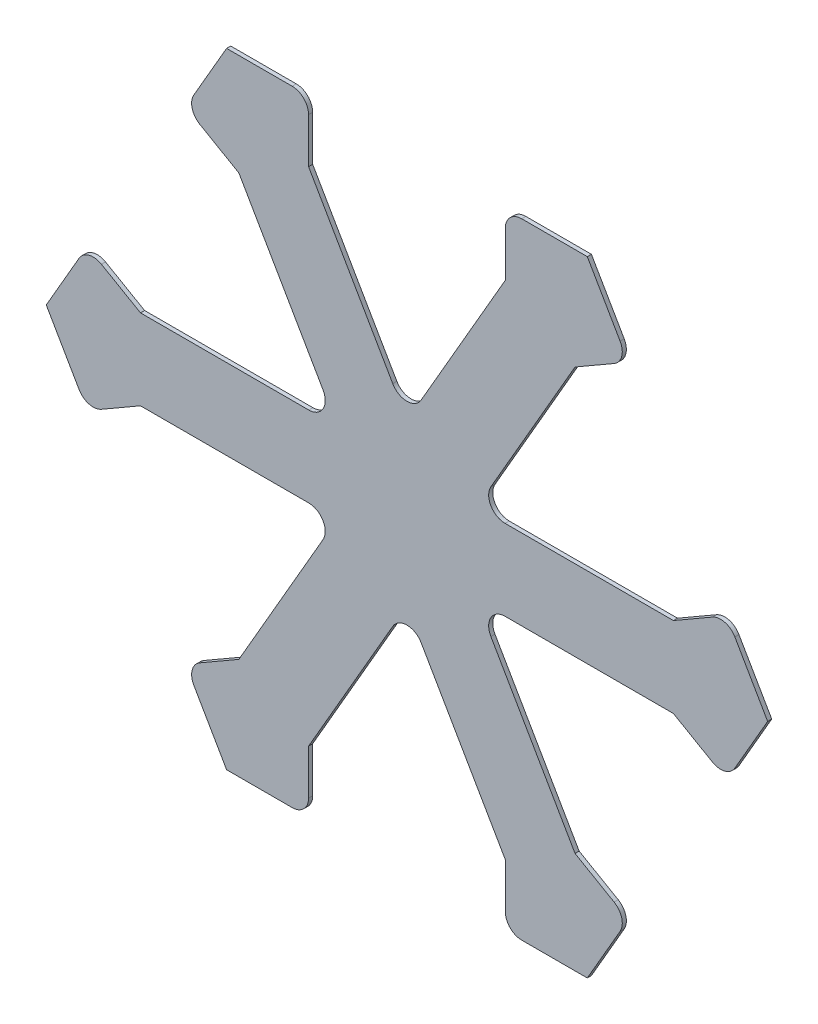
SolidWorks part; units mm, degrees
material "1.0037 (S235JR)"
ref_plane "Plan de face" through (0, 0, 0) normal (0, 0, 1) x (1, 0, 0)
ref_plane "Plan de dessus" through (0, 0, 0) normal (0, 1, 0) x (1, 0, 0)
ref_plane "Plan de droite" through (0, 0, 0) normal (1, 0, 0) x (0, 0, -1)
sketch "Esquisse2" plane through (0, 0, 0) normal (0, 0, 1) x (1, 0, 0)
  line L0 (-440, 0) -> (-400, -69.282)
  line L1 (-372.6795, -76.6025) -> (-325.0481, -49.1025)
  line L3 (-400, 69.282) -> (-440, 0)
  line L4 (-372.6795, 76.6025) -> (-325.0481, 49.1025)
  line L25 (-325.0481, 49.1025) -> (-119.6891, 49.1025)
  line L36 (-119.6891, -49.1025) -> (-325.0481, -49.1025)
  line L37 (-85.0481, 49.1025) -> (-85.0481, -49.1025) construction
  line L38 (-220, 381.0512) -> (-260, 311.7691)
  line L39 (-252.6795, 284.4486) -> (-205.0481, 256.9486)
  line L40 (-140, 381.0512) -> (-220, 381.0512)
  line L41 (-120, 361.0512) -> (-120, 306.0512)
  line L42 (-120, 306.0512) -> (-17.3205, 128.2051)
  line L43 (-102.3686, 79.1025) -> (-205.0481, 256.9486)
  line L44 (0, 98.2051) -> (-85.0481, 49.1025) construction
  line L45 (220, 381.0512) -> (140, 381.0512)
  line L46 (120, 361.0512) -> (120, 306.0512)
  line L47 (260, 311.7691) -> (220, 381.0512)
  line L48 (252.6795, 284.4486) -> (205.0481, 256.9486)
  line L49 (205.0481, 256.9486) -> (102.3686, 79.1025)
  line L50 (17.3205, 128.2051) -> (120, 306.0512)
  line L51 (85.0481, 49.1025) -> (0, 98.2051) construction
  line L52 (440, 0) -> (400, 69.282)
  line L53 (372.6795, 76.6025) -> (325.0481, 49.1025)
  line L54 (400, -69.282) -> (440, 0)
  line L55 (372.6795, -76.6025) -> (325.0481, -49.1025)
  line L56 (325.0481, -49.1025) -> (119.6891, -49.1025)
  line L57 (119.6891, 49.1025) -> (325.0481, 49.1025)
  line L58 (85.0481, -49.1025) -> (85.0481, 49.1025) construction
  line L59 (220, -381.0512) -> (260, -311.7691)
  line L60 (252.6795, -284.4486) -> (205.0481, -256.9486)
  line L61 (140, -381.0512) -> (220, -381.0512)
  line L62 (120, -361.0512) -> (120, -306.0512)
  line L63 (120, -306.0512) -> (17.3205, -128.2051)
  line L64 (102.3686, -79.1025) -> (205.0481, -256.9486)
  line L65 (0, -98.2051) -> (85.0481, -49.1025) construction
  line L66 (-220, -381.0512) -> (-140, -381.0512)
  line L67 (-120, -361.0512) -> (-120, -306.0512)
  line L68 (-260, -311.7691) -> (-220, -381.0512)
  line L69 (-252.6795, -284.4486) -> (-205.0481, -256.9486)
  line L70 (-205.0481, -256.9486) -> (-102.3686, -79.1025)
  line L71 (-17.3205, -128.2051) -> (-120, -306.0512)
  line L72 (-85.0481, -49.1025) -> (0, -98.2051) construction
  line L73 (-223.2362, 330.4459) -> (-397.7927, 28.1052) construction
  arc A0 (102.3686, 79.1025) -> (119.6891, 49.1025) centre (119.6891, 69.1025) ccw
  arc A1 (119.6891, -49.1025) -> (102.3686, -79.1025) centre (119.6891, -69.1025) ccw
  arc A2 (17.3205, -128.2051) -> (-17.3205, -128.2051) centre (0, -138.2051) ccw
  arc A3 (-102.3686, -79.1025) -> (-119.6891, -49.1025) centre (-119.6891, -69.1025) ccw
  arc A4 (-17.3205, 128.2051) -> (17.3205, 128.2051) centre (0, 138.2051) ccw
  arc A5 (-102.3686, 79.1025) -> (-119.6891, 49.1025) centre (-119.6891, 69.1025) cw
  arc A6 (-260, -311.7691) -> (-252.6795, -284.4486) centre (-242.6795, -301.7691) cw
  arc A7 (-140, -381.0512) -> (-120, -361.0512) centre (-140, -361.0512) ccw
  arc A8 (140, -381.0512) -> (120, -361.0512) centre (140, -361.0512) cw
  arc A9 (260, -311.7691) -> (252.6795, -284.4486) centre (242.6795, -301.7691) ccw
  arc A10 (400, -69.282) -> (372.6795, -76.6025) centre (382.6795, -59.282) cw
  arc A11 (400, 69.282) -> (372.6795, 76.6025) centre (382.6795, 59.282) ccw
  arc A12 (260, 311.7691) -> (252.6795, 284.4486) centre (242.6795, 301.7691) cw
  arc A13 (140, 381.0512) -> (120, 361.0512) centre (140, 361.0512) ccw
  arc A14 (-140, 381.0512) -> (-120, 361.0512) centre (-140, 361.0512) cw
  arc A15 (-260, 311.7691) -> (-252.6795, 284.4486) centre (-242.6795, 301.7691) ccw
  arc A16 (-400, -69.282) -> (-372.6795, -76.6025) centre (-382.6795, -59.282) ccw
  arc A17 (-372.6795, 76.6025) -> (-400, 69.282) centre (-382.6795, 59.282) ccw
  point P2 (-85.0481, 0)
  point P6 (0, 0)
  point P12 (-42.524, 73.6538)
  point P21 (42.524, 73.6538)
  point P29 (85.0481, 0)
  point P37 (0.1928, -8.2278)
  point P38 (42.524, -73.6538)
  point P47 (-42.524, -73.6538)
  point P53 (0, 0)
  point P88 (-390, -86.6025)
  point P91 (-390, 86.6025)
  dimension "D8" = 6
  dimension "D9" = 20
  dimension "D10" = 20
  dimension "D1" = 120
  dimension "D2" = 100
  dimension "D3" = 100
  dimension "D4" = 75
  dimension "D5" = 75
  dimension "D6" = 90
  dimension "D7" = 440
extrude "Boss.-Extru.2" add sketch "Esquisse2" along normal blind 5 contours L71 L63 L62 L61 L59 L60 L64 L56 L55 L54 L52 L53 L57 L49 L48 L47 L45 L46 L50 L42 L41 L40 L38 L39 L43 L25 L4 L3 L0 L1 L36 L70 L69 L68 L66 L67
